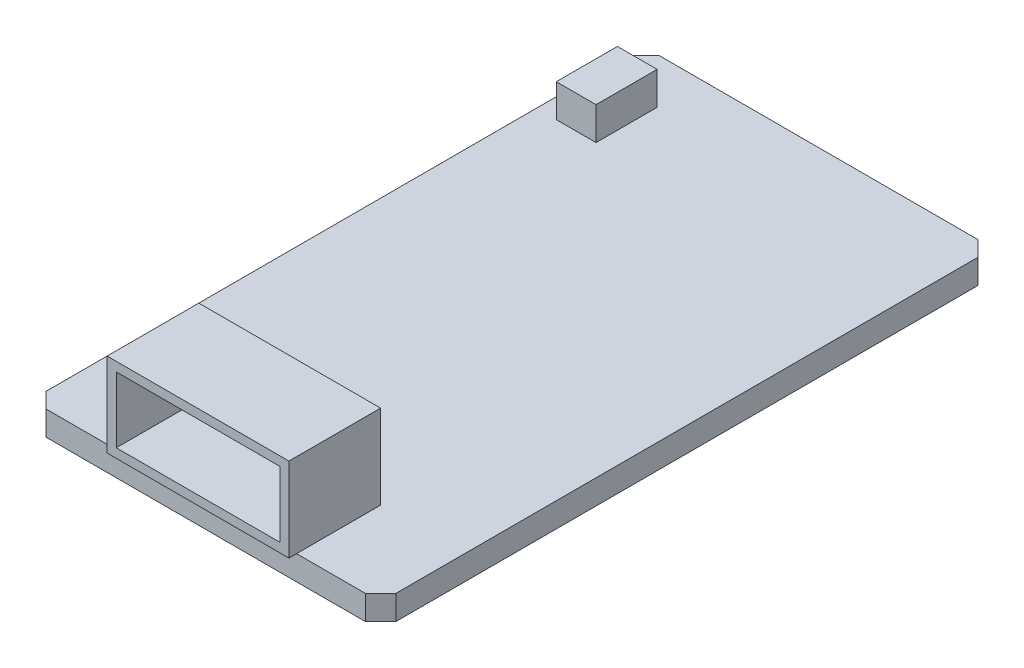
SolidWorks part; units mm, degrees
ref_plane "Front Plane" through (0, 0, 0) normal (0, 0, 1) x (1, 0, 0)
ref_plane "Top Plane" through (0, 0, 0) normal (0, 1, 0) x (1, 0, 0)
ref_plane "Right Plane" through (0, 0, 0) normal (1, 0, 0) x (0, 0, -1)
sketch "Sketch1" plane through (0, 0, 0) normal (0, 1, 0) x (1, 0, 0)
  line L1 (11.45, -20.05) -> (-11.45, -20.05)
  line L2 (11.45, -20.05) -> (11.45, 20.05)
  line L3 (11.45, 20.05) -> (-11.45, 20.05)
  line L4 (-11.45, -20.05) -> (-11.45, 20.05)
  line L5 (11.45, -20.05) -> (-11.45, 20.05) construction
  line L6 (11.45, 20.05) -> (-11.45, -20.05) construction
  point P0 (0, 0)
  dimension "D1" = 22.9
  dimension "D2" = 40.1
extrude "Boss-Extrude1" add sketch "Sketch1" along normal blind 1.6
sketch "Sketch2" plane through (0, 0, 20.05) normal (0, 0, 1) x (1, 0, 0)
  line L0 (-11.45, 1.6) -> (11.45, 1.6) construction
  line L1 (-5.95, 1.6) -> (5.95, 1.6)
  line L2 (-5.95, 1.6) -> (-5.95, 7.1)
  line L3 (-5.95, 7.1) -> (5.95, 7.1)
  line L4 (5.95, 1.6) -> (5.95, 7.1)
  point P6 (0, 1.6)
  dimension "D1" = 11.9
  dimension "D2" = 5.5
extrude "Boss-Extrude2" add sketch "Sketch2" along normal blind 0.5 and the other way blind 5.5 separate body
shell "Shell1" thickness 0.6
chamfer "Chamfer1" distance 1 angle 45 4 edges at (11.45, 0.8, -20.05) (-11.45, 0.8, -20.05) (11.45, 0.8, 20.05) (-11.45, 0.8, 20.05)
sketch "Sketch3" plane through (0, 1.6, 0) normal (0, 1, 0) x (1, 0, 0)
  line L0 (-11.45, 19.05) -> (-11.45, -19.05) construction
  line L1 (-10.15, 17.05) -> (-7.55, 17.05)
  line L2 (-10.15, 17.05) -> (-10.15, 13.05)
  line L3 (-10.15, 13.05) -> (-7.55, 13.05)
  line L4 (-7.55, 17.05) -> (-7.55, 13.05)
  line L5 (10.45, 20.05) -> (-10.45, 20.05) construction
  dimension "D1" = 4
  dimension "D2" = 2.6
  dimension "D3" = 1.3
  dimension "D4" = 3
extrude "Boss-Extrude3" add sketch "Sketch3" along normal blind 2.15
